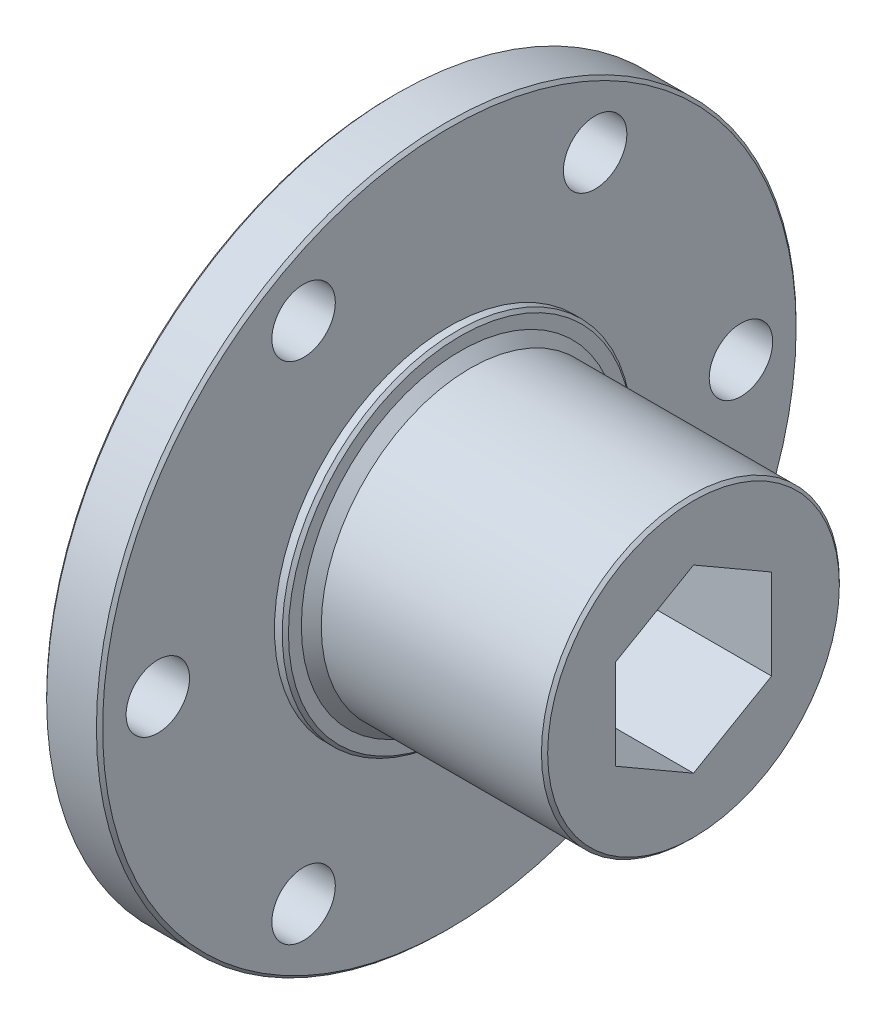
SolidWorks part; units mm, degrees
material "6061-T6 (SS)"
ref_plane "Front Plane" through (0, 0, 0) normal (0, 0, 1) x (1, 0, 0)
ref_plane "Top Plane" through (0, 0, 0) normal (0, 1, 0) x (1, 0, 0)
ref_plane "Right Plane" through (0, 0, 0) normal (1, 0, 0) x (0, 0, -1)
ref_plane "Plane1" through (0, 0, 0) normal (0, 0, -1) x (-1, 0, 0)
sketch "Sketch1" plane through (0, 0, 0) normal (0, 0, -1) x (-1, 0, 0)
  line L0 (13.9241, 28.575) -> (13.9241, 0)
  line L1 (13.9241, 0) -> (18.4961, 0)
  line L2 (18.4961, 0) -> (18.4961, 28.575)
  line L3 (18.4961, 28.575) -> (13.9241, 28.575)
  line L4 (13.9241, 0) -> (18.4961, 0) construction
revolve "Revolve1" add sketch "Sketch1" angle 360 about L4
sketch "Sketch2" plane through (-13.9241, 0, 0) normal (1, 0, 0) x (0, 0, -1)
  circle A0 centre (0, 0) radius 14.2875
extrude "Boss-Extrude1" add sketch "Sketch2" along normal blind 0.889
sketch "Sketch3" plane through (-13.0351, 0, 0) normal (1, 0, 0) x (0, 0, -1)
  circle A0 centre (0, 0) radius 12.9794
extrude "Boss-Extrude2" add sketch "Sketch3" along normal blind 0.8128 draft 45
sketch "Sketch4" plane through (-12.2223, 0, 0) normal (1, 0, 0) x (0, 0, -1)
  circle A0 centre (0, 0) radius 12.1666
extrude "Boss-Extrude3" add sketch "Sketch4" along normal blind 18.2372
sketch "Sketch5" plane through (-18.4961, 0, 0) normal (-1, 0, 0) x (0, 0, 1)
  circle A0 centre (0, 0) radius 14.2875
extrude "Boss-Extrude4" add sketch "Sketch5" along normal blind 0.889
sketch "Sketch6" plane through (-19.3851, 0, 0) normal (-1, 0, 0) x (0, 0, 1)
  line L0 (0, 7.3617) -> (-6.3754, 3.6808)
  line L1 (-6.3754, 3.6808) -> (-6.3754, -3.6809)
  line L2 (-6.3754, -3.6809) -> (0, -7.3617)
  line L3 (0, -7.3617) -> (6.3754, -3.6809)
  line L4 (6.3754, -3.6809) -> (6.3754, 3.6808)
  line L5 (6.3754, 3.6808) -> (0, 7.3617)
extrude "Cut-Extrude1" cut sketch "Sketch6" against normal through all
hole_wizard "Hole1" positions "Sketch8" profile "Sketch7" legacy
sketch "Sketch8" plane through (-18.4961, 0, 0) normal (-1, 0, 0) x (0, 0, 1)
  point P0 (11.9063, 20.6222)
  point P1 (-23.8125, 0)
  point P2 (11.9062, -20.6222)
  point P3 (-11.9063, -20.6222)
  point P4 (-11.9062, 20.6222)
  point P5 (23.8125, 0)
sketch "Sketch7" plane through (-18.4961, 20.6222, 11.9063) normal (0, 1, 0) x (0, 0, 1)
  line L0 (0, 0) -> (0, 24.511)
  line L1 (0, 24.511) -> (2.5908, 24.511)
  line L2 (2.5908, 24.511) -> (2.5908, 0)
  line L3 (2.5908, 0) -> (0, 0)
  line L4 (0, 110) -> (0, -10) construction
  dimension "Diameter" = 5.1816
  dimension "Depth" = 24.511
chamfer "Chamfer1" distance 0.254 angle 45 5 edges at (-19.3851, 0, 14.2875) (6.0149, 0, -12.1666) (-18.4961, 0, 28.575) (-13.0351, 0, -14.2875) (-13.9241, 0, 28.575)
